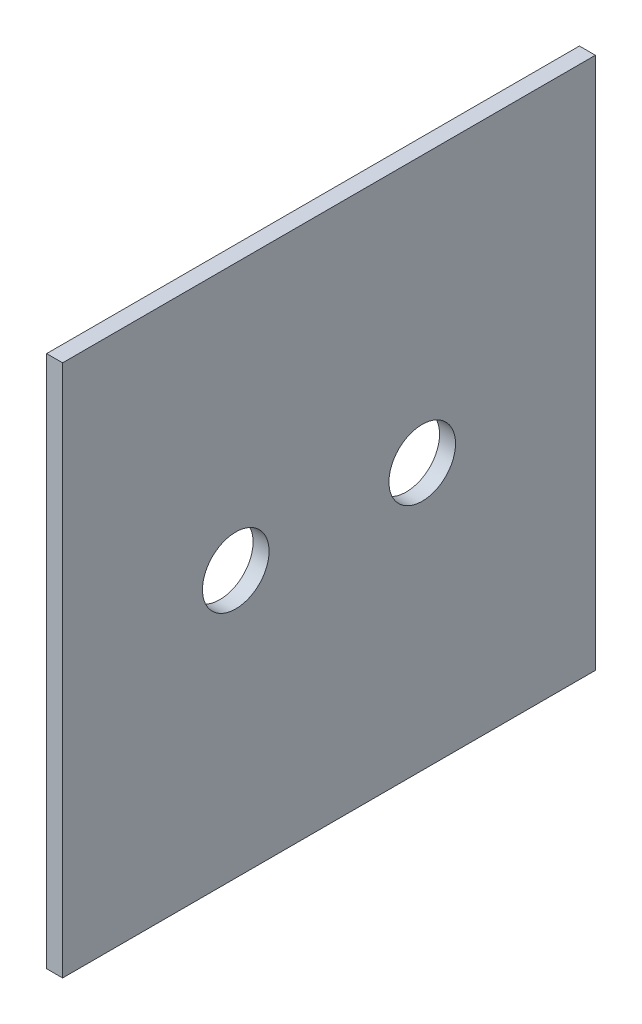
SolidWorks part; units mm, degrees
ref_plane "Front Plane" through (0, 0, 0) normal (0, 0, 1) x (1, 0, 0)
ref_plane "Top Plane" through (0, 0, 0) normal (0, 1, 0) x (1, 0, 0)
ref_plane "Right Plane" through (0, 0, 0) normal (1, 0, 0) x (0, 0, -1)
sketch "Sketch1" plane through (0, 0, 0) normal (1, 0, 0) x (0, 0, -1)
  line L1 (-92.7174, 133.4592) -> (107.2826, 133.4592)
  line L2 (-92.7174, 133.4592) -> (-92.7174, -66.5408)
  line L3 (-92.7174, -66.5408) -> (107.2826, -66.5408)
  line L4 (107.2826, 133.4592) -> (107.2826, -66.5408)
  circle A0 centre (42.2826, 33.4592) radius 12.5
  circle A1 centre (-27.7174, 33.4592) radius 12.5
  dimension "D1" = 200
  dimension "D2" = 200
  dimension "D3" = 100
  dimension "D4" = 100
  dimension "D5" = 65
  dimension "D6" = 65
extrude "Boss-Extrude1" add sketch "Sketch1" along normal blind 6
